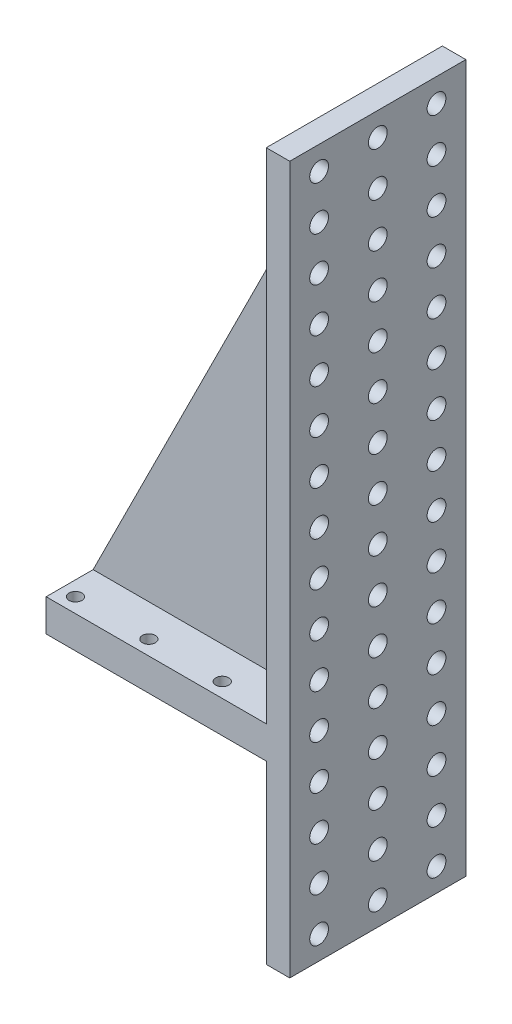
SolidWorks part; units mm, degrees
ref_plane "Front Plane" through (0, 0, 0) normal (0, 0, 1) x (1, 0, 0)
ref_plane "Top Plane" through (0, 0, 0) normal (0, 1, 0) x (1, 0, 0)
ref_plane "Right Plane" through (0, 0, 0) normal (1, 0, 0) x (0, 0, -1)
sketch "Sketch1" plane through (0, 0, 0) normal (0, 1, 0) x (1, 0, 0)
  line L1 (37.5, -30) -> (-37.5, -30)
  line L2 (37.5, -30) -> (37.5, 30)
  line L3 (37.5, 30) -> (-37.5, 30)
  line L4 (-37.5, -30) -> (-37.5, 30)
  line L5 (37.5, -30) -> (-37.5, 30) construction
  line L6 (37.5, 30) -> (-37.5, -30) construction
  circle A0 centre (-7.5, 25) radius 2.2
  circle A2 centre (-7.5, -25) radius 2.2
  circle A3 centre (17.5, 25) radius 2.2
  circle A4 centre (17.5, 0) radius 2.2
  circle A5 centre (17.5, -25) radius 2.2
  circle A6 centre (-32.5, 25) radius 2.2
  circle A9 centre (-32.5, 0) radius 2.2
  circle A10 centre (-32.5, -25) radius 2.2
  circle A11 centre (-7.5, 0) radius 2.2
  point P0 (0, 0)
  dimension "D3" = 4.4
  dimension "D4" = 4.4
  dimension "D5" = 4.4
  dimension "D12" = 4.4
  dimension "D15" = 4.4
  dimension "D16" = 4.4
  dimension "D21" = 4.4
  dimension "D26" = 4.4
  dimension "D27" = 4.4
  dimension "D1" = 75
  dimension "D2" = 60
  dimension "D6" = 5
  dimension "D7" = 30
  dimension "D8" = 30
  dimension "D9" = 5
  dimension "D10" = 5
  dimension "D11" = 55
  dimension "D13" = 55
  dimension "D14" = 30
  dimension "D17" = 55
  dimension "D18" = 55
  dimension "D19" = 5
  dimension "D20" = 5
  dimension "D22" = 5
  dimension "D23" = 30
  dimension "D24" = 55
  dimension "D25" = 5
  dimension "D28" = 30
  dimension "D29" = 30
extrude "Boss-Extrude1" add sketch "Sketch1" along normal blind 11
sketch "Sketch2" plane through (37.5, 0, 0) normal (1, 0, 0) x (0, 0, -1)
  line L0 (-30, 0) -> (30, 0) construction
  line L1 (-30, 181) -> (30, 181)
  line L2 (-30, 181) -> (-30, -60)
  line L3 (-30, -60) -> (30, -60)
  line L4 (30, 181) -> (30, -60)
  line L5 (-30, 11) -> (30, 11) construction
  line L6 (-30, 11) -> (-30, 0) construction
  dimension "D1" = 60
  dimension "D2" = 170
  dimension "D3" = 60
  dimension "D4" = 0
extrude "Boss-Extrude2" add sketch "Sketch2" along normal blind 8
sketch "Sketch4" plane through (0, 11, 0) normal (0, 1, 0) x (1, 0, 0)
  line L0 (-37.5, -30) -> (37.5, -30) construction
  line L1 (37.5, 14) -> (-37.5, 14)
  line L2 (37.5, 14) -> (37.5, 8)
  line L3 (37.5, 8) -> (-37.5, 8)
  line L4 (-37.5, 14) -> (-37.5, 8)
  line L5 (37.5, -8) -> (-37.5, -8)
  line L6 (37.5, -8) -> (37.5, -14)
  line L7 (37.5, -14) -> (-37.5, -14)
  line L8 (-37.5, -8) -> (-37.5, -14)
  line L9 (37.5, 30) -> (-37.5, 30) construction
  line L10 (37.5, -30) -> (37.5, 30) construction
  point P8 (0, -14)
  dimension "D1" = 75
  dimension "D2" = 6
  dimension "D3" = 75
  dimension "D4" = 6
  dimension "D5" = 16
  dimension "D6" = 16
  dimension "D7" = 0
  dimension "D8" = 0
extrude "Boss-Extrude3" add sketch "Sketch4" along normal blind 150
sketch "Sketch5" plane through (0, 0, 14) normal (0, 0, 1) x (1, 0, 0)
  line L3 (37.5, 161) -> (-37.5, 161)
  line L4 (37.5, 161) -> (37.5, 11) construction
  line L5 (-37.5, 161) -> (37.5, 161) construction
  line L6 (-37.5, 161) -> (-37.5, 11)
  line L7 (-37.5, 11) -> (37.5, 161)
extrude "Cut-Extrude1" cut sketch "Sketch5" against normal blind 28
sketch "Sketch6" plane through (45.5, 0, 0) normal (1, 0, 0) x (0, 0, -1)
  line L0 (0, 181) -> (0, -60) construction
  line L1 (30, 181) -> (-30, 181) construction
  line L2 (-30, -60) -> (30, -60) construction
  line L3 (20, 181) -> (20, -60) construction
  line L4 (-20, 181) -> (-20, -60) construction
  line L5 (-30, 173) -> (30, 173) construction
  line L6 (-30, 181) -> (-30, -60) construction
  line L7 (30, -60) -> (30, 181) construction
  line L8 (-30, 158) -> (30, 158) construction
  line L9 (-30, 143) -> (30, 143) construction
  line L10 (-30, 128) -> (30, 128) construction
  line L11 (-30, 113) -> (30, 113) construction
  line L12 (-30, 98) -> (30, 98) construction
  line L13 (-30, 83) -> (30, 83) construction
  line L14 (-30, 68) -> (30, 68) construction
  line L15 (30, 53) -> (-30, 53) construction
  line L16 (-30, 38) -> (30, 38) construction
  line L17 (30, 23) -> (-30, 23) construction
  line L18 (-30, 8) -> (30, 8) construction
  line L19 (-30, -7) -> (30, -7) construction
  line L20 (-30, -22) -> (30, -22) construction
  line L21 (30, -37) -> (-30, -37) construction
  line L22 (-30, -52) -> (30, -52) construction
  circle A1 centre (-20, 173) radius 3.2
  circle A2 centre (0, 173) radius 3.2
  circle A3 centre (20, 173) radius 3.2
  circle A4 centre (0, 158) radius 3.2
  circle A5 centre (-20, 158) radius 3.2
  circle A6 centre (20, 158) radius 3.2
  circle A7 centre (-20, 143) radius 3.2
  circle A8 centre (0, 143) radius 3.2
  circle A9 centre (20, 143) radius 3.2
  circle A17 centre (-20, 128) radius 3.2
  circle A18 centre (0, 128) radius 3.2
  circle A19 centre (20, 128) radius 3.2
  circle A20 centre (-20, 113) radius 3.2
  circle A21 centre (0, 113) radius 3.2
  circle A22 centre (20, 113) radius 3.2
  circle A23 centre (20, 98) radius 3.2
  circle A24 centre (0, 98) radius 3.2
  circle A25 centre (-20, 98) radius 3.2
  circle A26 centre (-20, 83) radius 3.2
  circle A27 centre (0, 83) radius 3.2
  circle A28 centre (20, 83) radius 3.2
  circle A29 centre (20, 68) radius 3.2
  circle A30 centre (0, 68) radius 3.2
  circle A31 centre (-20, 68) radius 3.2
  circle A32 centre (-20, 53) radius 3.2
  circle A33 centre (0, 53) radius 3.2
  circle A34 centre (20, 53) radius 3.2
  circle A35 centre (20, 38) radius 3.2
  circle A36 centre (0, 38) radius 3.2
  circle A37 centre (-20, 38) radius 3.2
  circle A38 centre (-20, 23) radius 3.2
  circle A39 centre (0, 23) radius 3.2
  circle A40 centre (20, 23) radius 3.2
  circle A41 centre (20, 8) radius 3.2
  circle A42 centre (-20, 8) radius 3.2
  circle A43 centre (0, 8) radius 3.2
  circle A44 centre (-20, -7) radius 3.2
  circle A45 centre (0, -7) radius 3.2
  circle A46 centre (20, -7) radius 3.2
  circle A47 centre (20, -22) radius 3.2
  circle A48 centre (0, -22) radius 3.2
  circle A49 centre (-20, -22) radius 3.2
  circle A50 centre (-20, -37) radius 3.2
  circle A51 centre (0, -37) radius 3.2
  circle A52 centre (20, -37) radius 3.2
  circle A53 centre (20, -52) radius 3.2
  circle A54 centre (0, -52) radius 3.2
  circle A55 centre (-20, -52) radius 3.2
  dimension "D23" = 6.4
  dimension "D1" = 20
  dimension "D2" = 20
  dimension "D3" = 8
  dimension "D4" = 15
  dimension "D5" = 15
  dimension "D6" = 15
  dimension "D7" = 15
  dimension "D8" = 15
  dimension "D9" = 15
  dimension "D10" = 15
  dimension "D11" = 15
  dimension "D12" = 15
  dimension "D13" = 15
  dimension "D14" = 15
  dimension "D15" = 15
  dimension "D16" = 15
  dimension "D17" = 15
  dimension "D18" = 15
extrude "Cut-Extrude2" cut sketch "Sketch6" against normal blind 8
